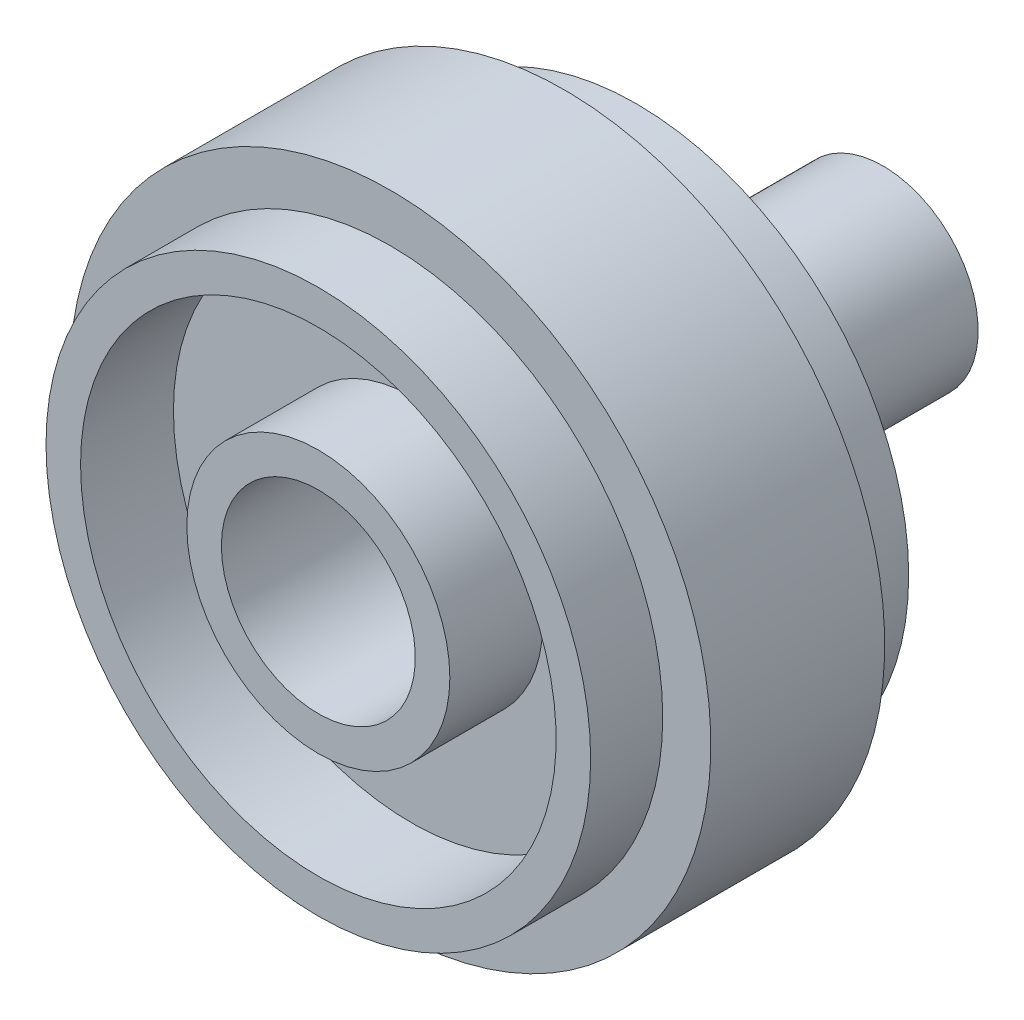
SolidWorks part; units mm, degrees
material "ABS"
ref_plane "Front Plane" through (0, 0, 0) normal (0, 0, 1) x (1, 0, 0)
ref_plane "Top Plane" through (0, 0, 0) normal (0, 1, 0) x (1, 0, 0)
ref_plane "Right Plane" through (0, 0, 0) normal (1, 0, 0) x (0, 0, -1)
sketch "Sketch1" plane through (0, 0, 0) normal (1, 0, 0) x (0, 0, -1)
  line L0 (0, 0) -> (-12.2789, 0) construction
  line L1 (0, 0) -> (0, 10.9537) construction
  line L2 (2.9718, 10.9537) -> (-2.9718, 10.9537)
  line L3 (-2.9718, 10.9537) -> (-2.9718, 9.3091)
  line L4 (-2.9718, 9.3091) -> (-5.4356, 9.3091)
  line L5 (-5.4356, 9.3091) -> (-5.4356, 8.128)
  line L6 (-5.4356, 8.128) -> (-2.2606, 8.128)
  line L7 (-2.2606, 8.128) -> (-2.2606, 4.4958)
  line L8 (-2.2606, 4.4958) -> (-5.4356, 4.4958)
  line L9 (-5.4356, 4.4958) -> (-5.4356, 3.3147)
  line L10 (-5.4356, 3.3147) -> (1.1938, 3.3147)
  line L11 (1.1938, 3.3147) -> (1.1938, 1.5557)
  line L12 (1.1938, 1.5557) -> (13.8684, 1.5557)
  line L13 (13.8684, 1.5557) -> (13.8684, 3.2512)
  line L14 (13.8684, 3.2512) -> (2.2225, 3.2512)
  line L15 (2.2225, 3.2512) -> (2.2225, 4.4958)
  line L16 (2.2225, 4.4958) -> (-0.5207, 4.4958)
  line L17 (-0.5207, 4.4958) -> (-0.5207, 8.128)
  line L18 (-0.5207, 8.128) -> (5.4356, 8.128)
  line L19 (5.4356, 8.128) -> (5.4356, 9.3091)
  line L20 (5.4356, 9.3091) -> (2.9718, 9.3091)
  line L21 (2.9718, 9.3091) -> (2.9718, 10.9537)
  point P17 (0.7897, 4.4162)
  point P25 (0, 3.742)
  point P26 (0, 3.8993)
  point P27 (0, 4.551)
  dimension "D1" = 21.9075
  dimension "D2" = 18.6182
  dimension "D3" = 5.9436
  dimension "D4" = 10.8712
  dimension "D5" = 1.1811
  dimension "D6" = 1.1811
  dimension "D7" = 5.9944
  dimension "D8" = 6.6294
  dimension "D9" = 3.175
  dimension "D10" = 3.1115
  dimension "D11" = 6.5024
  dimension "D12" = 11.6459
  dimension "D13" = 14.3891
  dimension "D14" = 5.9563
revolve "Revolve1" add sketch "Sketch1" angle 360 about L0
